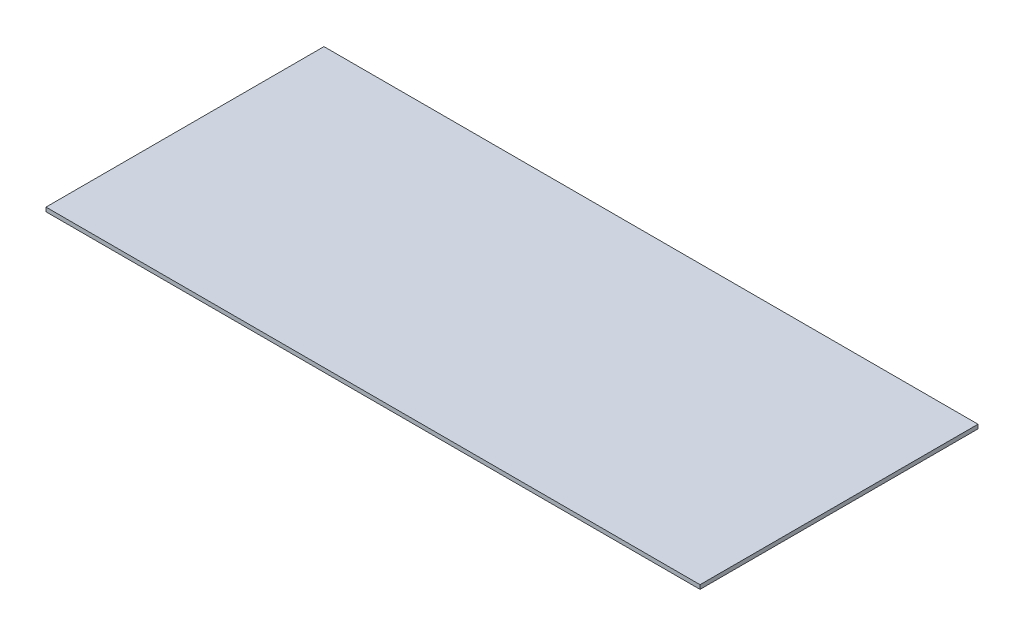
SolidWorks part; units mm, degrees
ref_plane "Front Plane" through (0, 0, 0) normal (0, 0, 1) x (1, 0, 0)
ref_plane "Top Plane" through (0, 0, 0) normal (0, 1, 0) x (1, 0, 0)
ref_plane "Right Plane" through (0, 0, 0) normal (1, 0, 0) x (0, 0, -1)
sketch "Sketch2" plane through (0, 0, 0) normal (0, 1, 0) x (1, 0, 0)
  line L6 (-254, -107.95) -> (254, -107.95)
  line L7 (-254, -107.95) -> (-254, 107.95)
  line L8 (-254, 107.95) -> (254, 107.95)
  line L17 (254, -107.95) -> (254, 107.95)
  line L18 (-254, -107.95) -> (254, 107.95) construction
  line L19 (-254, 107.95) -> (254, -107.95) construction
  point P0 (0, 0)
  point P1 (29.4161, 75.2471)
  point P9 (0, 0)
  dimension "D1" = 215.9
  dimension "D2" = 508
extrude "Boss-Extrude2" add sketch "Sketch2" along normal blind 3.175
